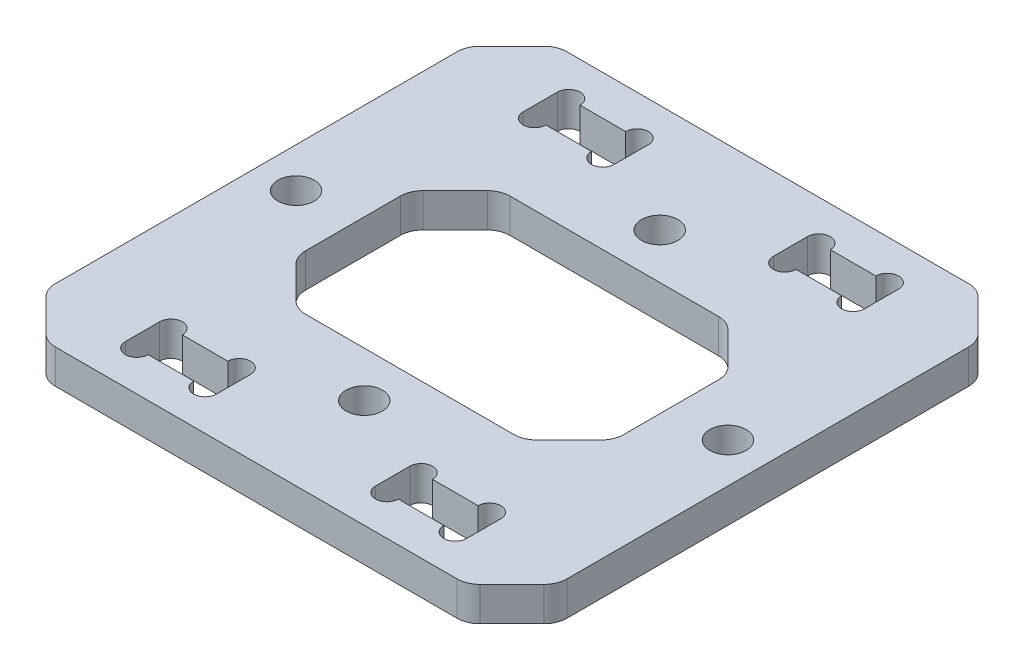
SolidWorks part; units mm, degrees
material "Thornel Mat VMA"
ref_plane "前视基准面" through (0, 0, 0) normal (0, 0, 1) x (1, 0, 0)
ref_plane "上视基准面" through (0, 0, 0) normal (0, 1, 0) x (1, 0, 0)
ref_plane "右视基准面" through (0, 0, 0) normal (1, 0, 0) x (0, 0, -1)
other "Configuration Table"
sketch "草图1" plane through (0, 0, 0) normal (0, 1, 0) x (1, 0, 0)
  line L1 (-22.5, 22.5) -> (22.5, 22.5)
  line L2 (-22.5, 22.5) -> (-22.5, -22.5)
  line L3 (-22.5, -22.5) -> (22.5, -22.5)
  line L4 (22.5, 22.5) -> (22.5, -22.5)
  line L5 (-22.5, 22.5) -> (22.5, -22.5) construction
  line L6 (-22.5, -22.5) -> (22.5, 22.5) construction
  circle A0 centre (19, 0) radius 1.6
  circle A1 centre (-19, 0) radius 1.6
  point P0 (0, 0)
  dimension "D3" = 3.2
  dimension "D1" = 19
  dimension "D2" = 38
  dimension "D4" = 45
extrude "凸台-拉伸1" add sketch "草图1" along normal blind 3
sketch "草图2" plane through (0, 3, 0) normal (0, 1, 0) x (1, 0, 0)
  line L0 (7, -19.005) -> (-7, -19.005) construction
  line L1 (-15.01, -15.995) -> (-7, -15.995)
  line L2 (-15.01, -15.995) -> (-15.01, -19.005)
  line L3 (-15.01, -19.005) -> (-7, -19.005)
  line L4 (-7, -15.995) -> (-7, -19.005)
  line L5 (7, -15.995) -> (15.01, -15.995)
  line L6 (7, -15.995) -> (7, -19.005)
  line L7 (7, -19.005) -> (15.01, -19.005)
  line L8 (15.01, -15.995) -> (15.01, -19.005)
  line L9 (0, 0) -> (-33.3693, 0) construction
  line L10 (-15.01, 19.005) -> (-7, 19.005)
  line L11 (-7, 15.995) -> (-7, 19.005)
  line L12 (-15.01, 15.995) -> (-7, 15.995)
  line L13 (-15.01, 15.995) -> (-15.01, 19.005)
  line L14 (7, 19.005) -> (15.01, 19.005)
  line L15 (15.01, 15.995) -> (15.01, 19.005)
  line L16 (7, 15.995) -> (15.01, 15.995)
  line L17 (7, 15.995) -> (7, 19.005)
  point P8 (0, -19.005)
  dimension "D1" = 30.02
  dimension "D2" = 19.005
  dimension "D3" = 3.01
  dimension "D4" = 8.01
extrude "切除-拉伸1" cut sketch "草图2" against normal blind 3
sketch "草图4" plane through (0, 3, 0) normal (0, 1, 0) x (1, 0, 0)
  line L0 (-7, -15.995) -> (-15.01, -15.995) construction
  line L1 (-15.01, -19.005) -> (-7, -19.005) construction
  line L2 (0, -27.1301) -> (0, 0) construction
  line L3 (0, 0) -> (10.9414, 0) construction
  line L4 (7, -15.995) -> (7, -19.005) construction
  circle A0 centre (-14.01, -15.995) radius 1
  circle A1 centre (-14.01, -19.005) radius 1
  circle A2 centre (-8, -15.995) radius 1
  circle A3 centre (-8, -19.005) radius 1
  circle A4 centre (8, -19.005) radius 1
  circle A5 centre (8, -15.995) radius 1
  circle A6 centre (14.01, -19.005) radius 1
  circle A7 centre (14.01, -15.995) radius 1
  circle A8 centre (-8, 19.005) radius 1
  circle A9 centre (-8, 15.995) radius 1
  circle A10 centre (-14.01, 19.005) radius 1
  circle A11 centre (-14.01, 15.995) radius 1
  circle A12 centre (14.01, 15.995) radius 1
  circle A13 centre (14.01, 19.005) radius 1
  circle A14 centre (8, 15.995) radius 1
  circle A15 centre (8, 19.005) radius 1
  circle A16 centre (0, -13) radius 1.6
  circle A17 centre (0, 13) radius 1.6
  point P48 (7, -17.5)
  dimension "D1" = 2
  dimension "D3" = 3.2
  dimension "D2" = 4.5
extrude "切除-拉伸2" cut sketch "草图4" against normal blind 3
sketch "草图5" plane through (0, 3, 0) normal (0, 1, 0) x (1, 0, 0)
  line L1 (-14, 9) -> (14, 9)
  line L2 (-14, 9) -> (-14, -9)
  line L3 (-14, -9) -> (14, -9)
  line L4 (14, 9) -> (14, -9)
  line L5 (-14, 9) -> (14, -9) construction
  line L6 (-14, -9) -> (14, 9) construction
  circle A0 centre (0, -13) radius 1.6 construction
  circle A1 centre (19, 0) radius 1.6 construction
  point P0 (0, 0)
  dimension "D1" = 4
  dimension "D2" = 5
extrude "切除-拉伸3" cut sketch "草图5" against normal blind 3
chamfer "倒角1" distance 4 angle 45 8 edges at (-22.5, 1.5, -22.5) (22.5, 1.5, -22.5) (22.5, 1.5, 22.5) (-22.5, 1.5, 22.5) (-14, 1.5, 9) (14, 1.5, 9) (14, 1.5, -9) (-14, 1.5, -9)
fillet "圆角1" radius 2 16 edges at (-22.5, 1.5, 18.5) (-18.5, 1.5, 22.5) (22.5, 1.5, 18.5) (22.5, 1.5, -18.5) (18.5, 1.5, -22.5) (-18.5, 1.5, -22.5) (-22.5, 1.5, -18.5) (18.5, 1.5, 22.5) (14, 1.5, -5) (10, 1.5, -9) (-14, 1.5, -5) (-14, 1.5, 5) (-10, 1.5, 9) (10, 1.5, 9) (14, 1.5, 5) (-10, 1.5, -9)
